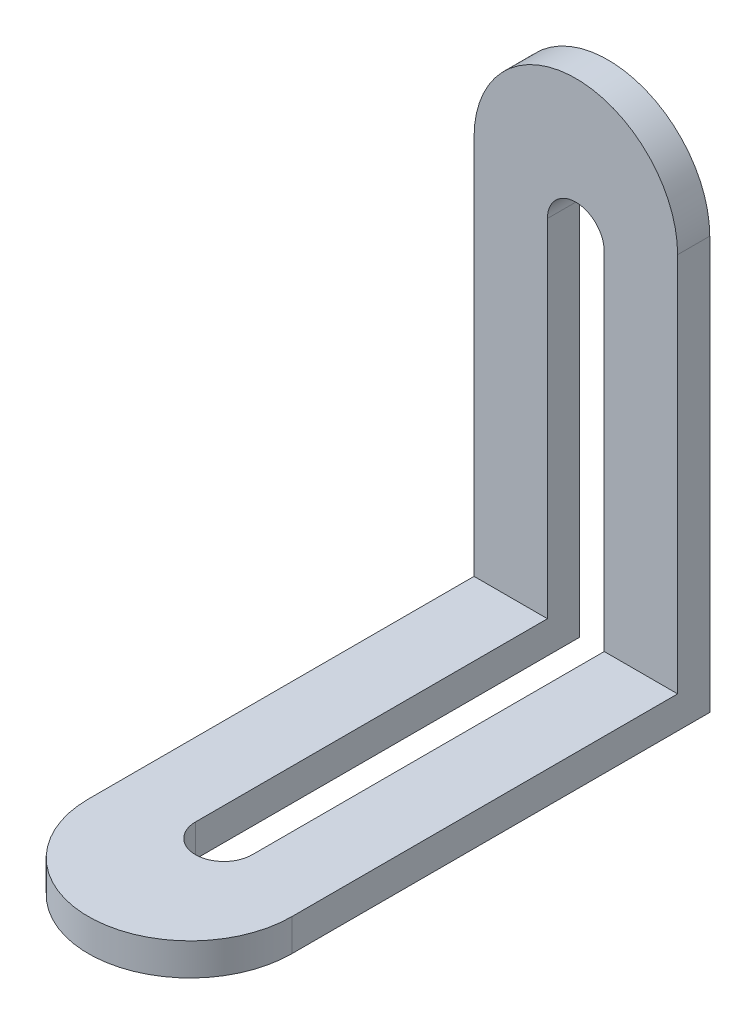
SolidWorks part; units mm, degrees
ref_plane "前视基准面" through (0, 0, 0) normal (0, 0, 1) x (1, 0, 0)
ref_plane "上视基准面" through (0, 0, 0) normal (0, 1, 0) x (1, 0, 0)
ref_plane "右视基准面" through (0, 0, 0) normal (1, 0, 0) x (0, 0, -1)
sketch "草图1" plane through (0, 0, 0) normal (0, 0, 1) x (1, 0, 0)
  line L1 (-36.3067, 25.7318) -> (-17.3067, 25.7318)
  line L2 (-36.3067, 25.7318) -> (-36.3067, -23.5927)
  line L3 (-36.3067, -23.5927) -> (-17.3067, -23.5927)
  line L4 (-17.3067, 25.7318) -> (-17.3067, -23.5927)
  line L5 (-29.4567, 11.7573) -> (-24.1567, 11.7573)
  line L6 (-29.4567, 11.7573) -> (-29.4567, -23.5927)
  line L7 (-29.4567, -23.5927) -> (-24.1567, -23.5927)
  line L8 (-24.1567, 11.7573) -> (-24.1567, -23.5927)
  circle A0 centre (-26.8067, 14.9073) radius 9.5
  circle A1 centre (-26.8067, 11.7573) radius 2.65
  point P12 (-26.8067, 25.7318)
  dimension "D1" = 19
  dimension "D3" = 5.3
  dimension "D2" = 38.5
  dimension "D4" = 5.3
  dimension "D5" = 3.15
extrude "凸台-拉伸1" add sketch "草图1" against normal blind 3 contours A1 L8 A0 L6 | A0 L2 L3 L6 | A0 L8 L3 L4
sketch "草图2" plane through (0, -23.5927, 0) normal (0, -1, 0) x (1, 0, 0)
  line L0 (-17.3067, -3) -> (-17.3067, 0) construction
  line L1 (-36.3067, -3) -> (-17.3067, -3)
  line L2 (-36.3067, -3) -> (-36.3067, 41.1161)
  line L3 (-36.3067, 41.1161) -> (-17.3067, 41.1161)
  line L4 (-17.3067, -3) -> (-17.3067, 41.1161)
  line L5 (-29.4567, -3) -> (-29.4567, 0) construction
  line L6 (-29.4567, 32.85) -> (-24.1567, 32.85)
  line L7 (-29.4567, 32.85) -> (-29.4567, -3)
  line L8 (-29.4567, -3) -> (-24.1567, -3)
  line L9 (-24.1567, 32.85) -> (-24.1567, -3)
  line L10 (-24.1567, -3) -> (-24.1567, 0) construction
  circle A0 centre (-26.8067, 36) radius 9.5
  circle A1 centre (-26.8067, 32.85) radius 2.65
  point P10 (-26.8067, 41.1161)
  line M4 (-29.4567, 0) -> (-36.3067, 0)
  dimension "D1" = 3.15
  dimension "D2" = 39
extrude "凸台-拉伸2" add sketch "草图2" against normal blind 3 contours A1 L9 A0 L3 L7 | L3 A0 | A0 L2 L7 M4 | A0 L9 L1 L4
